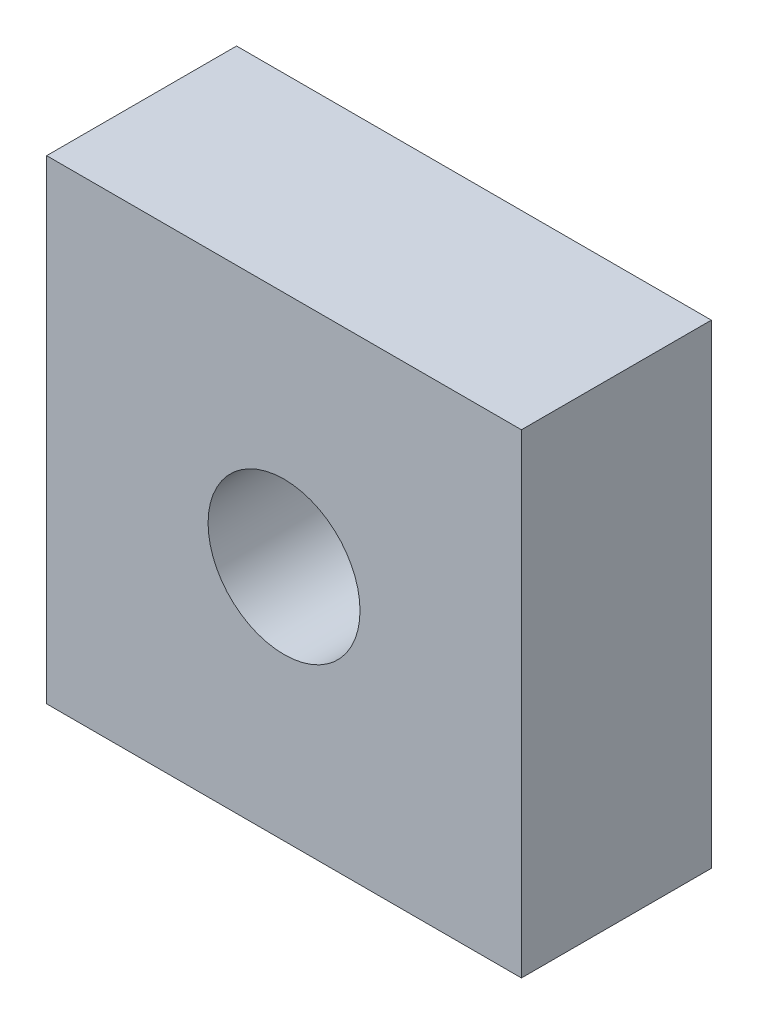
SolidWorks part; units mm, degrees
ref_plane "前视基准面" through (0, 0, 0) normal (0, 0, 1) x (1, 0, 0)
ref_plane "上视基准面" through (0, 0, 0) normal (0, 1, 0) x (1, 0, 0)
ref_plane "右视基准面" through (0, 0, 0) normal (1, 0, 0) x (0, 0, -1)
other "Configuration Table"
sketch "草图1" plane through (0, 0, 0) normal (0, 0, 1) x (1, 0, 0)
  line L1 (0, 0) -> (10, 0)
  line L2 (0, 0) -> (0, 10)
  line L3 (0, 10) -> (10, 10)
  line L4 (10, 0) -> (10, 10)
  circle A0 centre (5, 5) radius 1.6
  point P7 (5, 10)
  point P8 (0, 5)
  dimension "D3" = 3.2
  dimension "D1" = 10
  dimension "D2" = 10
extrude "凸台-拉伸1" add sketch "草图1" along normal blind 4
